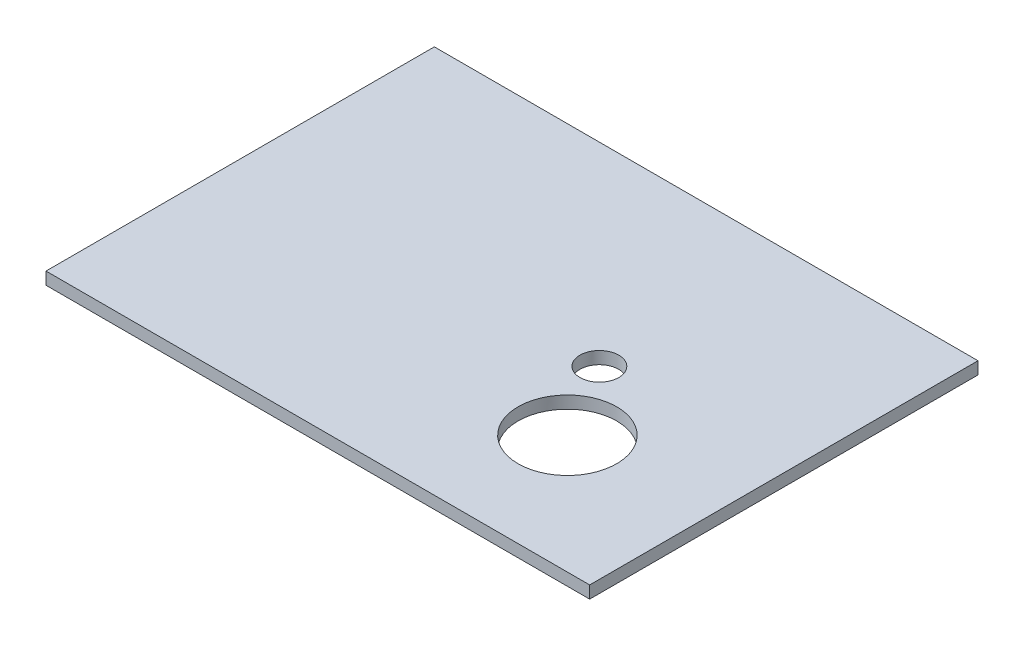
SolidWorks part; units mm, degrees
material "Oak"
ref_plane "Front Plane" through (0, 0, 0) normal (0, 0, 1) x (1, 0, 0)
ref_plane "Top Plane" through (0, 0, 0) normal (0, 1, 0) x (1, 0, 0)
ref_plane "Right Plane" through (0, 0, 0) normal (1, 0, 0) x (0, 0, -1)
sketch "Sketch1" plane through (0, 0, 0) normal (0, 1, 0) x (1, 0, 0)
  line L1 (0, 0) -> (140, 0)
  line L2 (0, 0) -> (0, 100)
  line L3 (0, 100) -> (140, 100)
  line L4 (140, 0) -> (140, 100)
  dimension "D1" = 140
  dimension "D2" = 100
extrude "Boss-Extrude1" add sketch "Sketch1" along normal blind 3.175
sketch "Sketch2" plane through (0, 3.175, 0) normal (0, 1, 0) x (1, 0, 0)
  line L0 (0, 50) -> (140, 50) construction
  line L1 (0, 100) -> (0, 0) construction
  line L2 (140, 0) -> (140, 100) construction
  line L3 (70, 100) -> (70, 0) construction
  line L4 (140, 100) -> (0, 100) construction
  line L5 (0, 0) -> (140, 0) construction
  line L6 (92.5, 50) -> (114.578, 11.7597) construction
  circle A0 centre (103.75, 30.5144) radius 12.705
  circle A1 centre (92.5, 50) radius 5
  point P12 (92.5, 50)
  point P13 (70, 50)
  dimension "D3" = 25.41
  dimension "D5" = 10
  dimension "D1" = 22.5
  dimension "D2" = 120
  dimension "D4" = 22.5
  dimension "D6" = 30.5144
  dimension "D7" = 36.25
extrude "Cut-Extrude1" cut sketch "Sketch2" against normal blind 10
